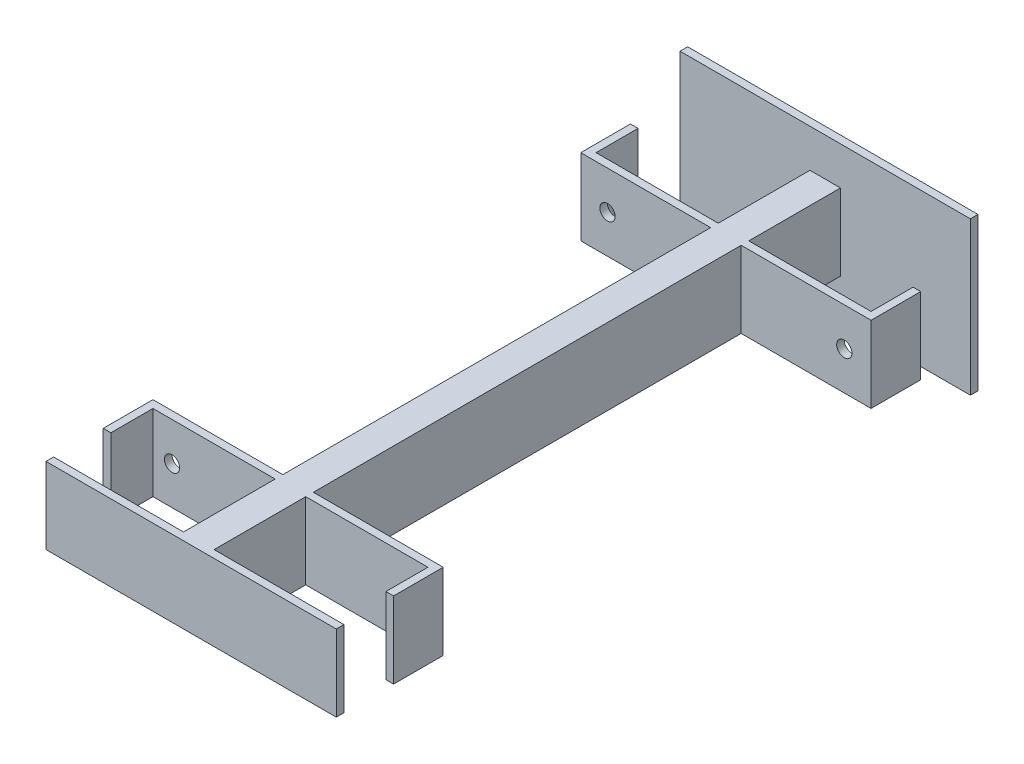
SolidWorks part; units mm, degrees
ref_plane "Front Plane" through (0, 0, 0) normal (0, 0, 1) x (1, 0, 0)
ref_plane "Top Plane" through (0, 0, 0) normal (0, 1, 0) x (1, 0, 0)
ref_plane "Right Plane" through (0, 0, 0) normal (1, 0, 0) x (0, 0, -1)
sketch "Sketch1" plane through (0, 0, 0) normal (0, 1, 0) x (1, 0, 0)
  line L3 (-68.3517, 159.8844) -> (-68.3517, 219.8844)
  line L4 (-68.3517, 219.8844) -> (-38.3517, 219.8844)
  line L6 (11.6483, 187.3844) -> (16.6483, 187.3844)
  line L7 (16.6483, 187.3844) -> (16.6483, 154.8844)
  line L8 (16.6483, 154.8844) -> (-68.3517, 154.8844)
  line L9 (-68.3517, 154.8844) -> (-68.3517, -125.1156)
  line L10 (-68.3517, -125.1156) -> (16.6483, -125.1156)
  line L14 (11.6483, -130.1156) -> (-68.3517, -130.1156)
  line L15 (-68.3517, -130.1156) -> (-68.3517, -190.1156)
  line L16 (-68.3517, -190.1156) -> (-38.3517, -190.1156)
  line L17 (-38.3517, -190.1156) -> (-38.3517, -195.1156)
  line L18 (-38.3517, -195.1156) -> (-118.3517, -195.1156)
  line L19 (-118.3517, -195.1156) -> (-118.3517, -190.1156)
  line L20 (-118.3517, -190.1156) -> (-88.3517, -190.1156)
  line L21 (-88.3517, -190.1156) -> (-88.3517, -130.1156)
  line L22 (-88.3517, -130.1156) -> (-168.3517, -130.1156)
  line L23 (-168.3517, -130.1156) -> (-168.3517, -157.6656)
  line L24 (-168.3517, -157.6656) -> (-173.3517, -157.6656)
  line L25 (-173.3517, -157.6656) -> (-173.3517, -125.1156)
  line L26 (-173.3517, -125.1156) -> (-88.3517, -125.1156)
  line L27 (-88.3517, -125.1156) -> (-88.3517, 154.8844)
  line L28 (-88.3517, 154.8844) -> (-173.3517, 154.8844)
  line L29 (-173.3517, 154.8844) -> (-173.3517, 187.3844)
  line L30 (-173.3517, 187.3844) -> (-168.3517, 187.3844)
  line L31 (-168.3517, 187.3844) -> (-168.3517, 159.8844)
  line L32 (-168.3517, 159.8844) -> (-88.3517, 159.8844)
  line L33 (-88.3517, 159.8844) -> (-88.3517, 219.8844)
  line L34 (-88.3517, 219.8844) -> (-118.3517, 219.8844)
  line L36 (-118.3517, 219.8844) -> (-118.3517, 224.8844)
  line L37 (-118.3517, 224.8844) -> (-38.3517, 224.8844)
  line L38 (-38.3517, 224.8844) -> (-38.3517, 219.8844)
  line L39 (-68.3517, 159.8844) -> (11.6483, 159.8844)
  line L40 (11.6483, 159.8844) -> (11.6483, 187.3844)
  line L41 (16.6483, -125.1156) -> (16.6483, -157.6156)
  line L42 (16.6483, -157.6156) -> (11.6483, -157.6156)
  line L43 (11.6483, -157.6156) -> (11.6483, -130.1156)
  point P0 (-78.3517, 224.8844)
  point P1 (-103.3517, 219.8844)
  point P38 (-78.3517, -195.1156)
  dimension "D1" = 20
  dimension "D2" = 410
  dimension "D3" = 410
  dimension "D4" = 280
  dimension "D5" = 5
  dimension "D6" = 32.5
  dimension "D7" = 60
  dimension "D8" = 85
  dimension "D9" = 60
  dimension "D10" = 60
  dimension "D11" = 5
  dimension "D12" = 5
  dimension "D13" = 5
  dimension "D14" = 5
  dimension "D15" = 32.5
  dimension "D16" = 5
  dimension "D17" = 5
  dimension "D18" = 5
  dimension "D19" = 5
  dimension "D20" = 32.5
  dimension "D21" = 32.55
  dimension "D22" = 5
  dimension "D23" = 80
  dimension "D24" = 80
  dimension "D25" = 80
  dimension "D26" = 80
  dimension "D27" = 85
  dimension "D28" = 80
  dimension "D29" = 30
  dimension "D30" = 85
  dimension "D31" = 85
  dimension "D32" = 30
  dimension "D33" = 30
extrude "Boss-Extrude1" add sketch "Sketch1" along normal blind 50
sketch "Sketch2" plane through (0, 0, -224.8844) normal (0, 0, -1) x (-1, 0, 0)
  line L0 (38.3517, 50) -> (38.3517, 0) construction
  line L1 (-16.6483, 75) -> (173.3517, 75)
  line L2 (-16.6483, 75) -> (-16.6483, -25)
  line L3 (-16.6483, -25) -> (173.3517, -25)
  line L4 (173.3517, 75) -> (173.3517, -25)
  point P6 (38.3517, 25)
  point P7 (-16.6483, 25)
  dimension "D1" = 100
extrude "Boss-Extrude2" add sketch "Sketch2" against normal blind 5
sketch "Sketch3" plane through (0, 0, 195.1156) normal (0, 0, 1) x (1, 0, 0)
  line L1 (-173.3517, 50) -> (16.6483, 50)
  line L2 (-173.3517, 50) -> (-173.3517, 0)
  line L3 (-173.3517, 0) -> (16.6483, 0)
  line L4 (16.6483, 50) -> (16.6483, 0)
extrude "Boss-Extrude3" add sketch "Sketch3" against normal blind 5
sketch "Sketch4" plane through (0, 0, 125.1156) normal (0, 0, -1) x (-1, 0, 0)
  line L0 (173.3517, 50) -> (173.3517, 0) construction
  line L1 (88.3517, 50) -> (173.3517, 50) construction
  circle A0 centre (155.8517, 25) radius 5
  dimension "D1" = 17.5
  dimension "D4" = 10
  dimension "D2" = 85
  dimension "D3" = 25
extrude "Cut-Extrude1" cut sketch "Sketch4" along normal blind 291 and the other way blind 20
sketch "Sketch5" plane through (0, 0, 125.1156) normal (0, 0, -1) x (-1, 0, 0)
  line L0 (-16.6483, 50) -> (-16.6483, 0) construction
  line L1 (-16.6483, 50) -> (68.3517, 50) construction
  circle A0 centre (0.8517, 25) radius 5
  dimension "D1" = 17.5
  dimension "D2" = 25
extrude "Cut-Extrude2" cut sketch "Sketch5" against normal blind 21 and the other way blind 291
